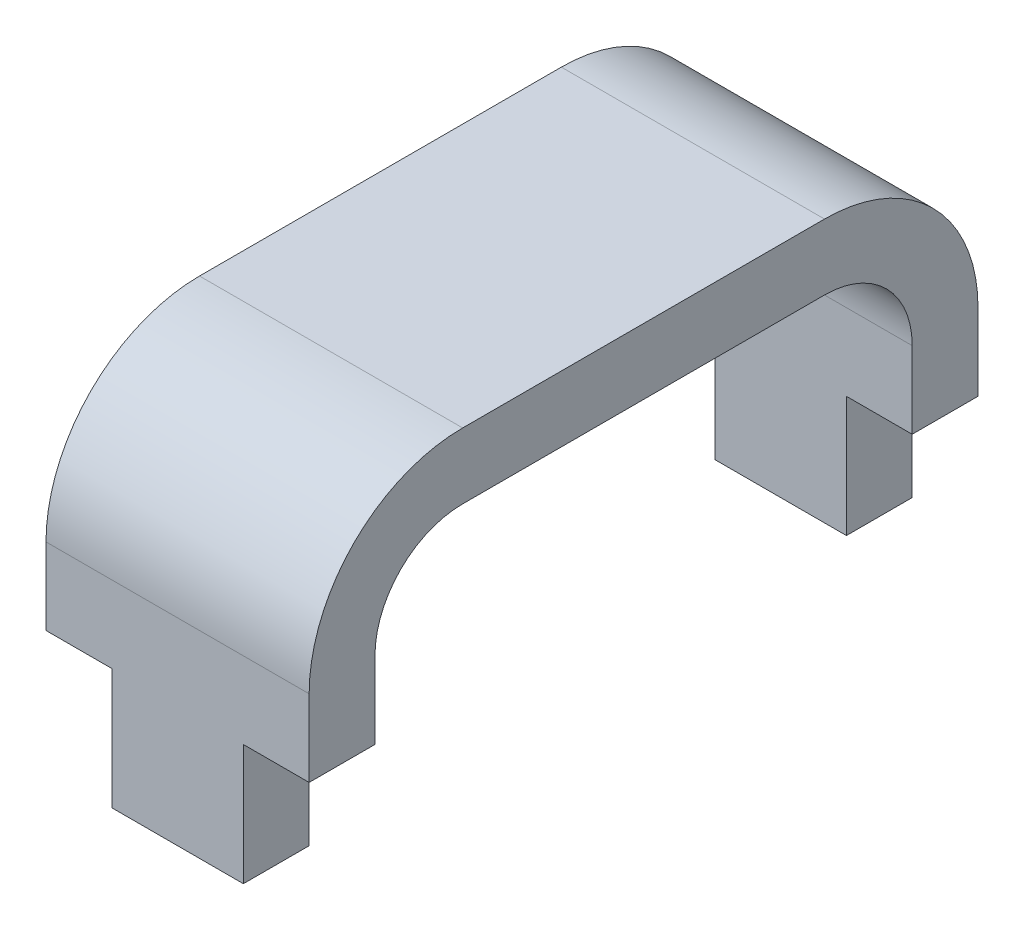
SolidWorks part; units mm, degrees
ref_plane "Front Plane" through (0, 0, 0) normal (0, 0, 1) x (1, 0, 0)
ref_plane "Top Plane" through (0, 0, 0) normal (0, 1, 0) x (1, 0, 0)
ref_plane "Right Plane" through (0, 0, 0) normal (1, 0, 0) x (0, 0, -1)
sketch "Sketch4" plane through (0, 0, 0) normal (1, 0, 0) x (0, 0, -1)
  line L0 (-13.3102, -12.5996) -> (-13.3102, -3.5996)
  line L1 (-9.3102, 3.4004) -> (7.1898, 3.4004)
  line L2 (-16.3102, -3.5996) -> (-16.3102, -12.5996)
  line L3 (-16.3102, -12.5996) -> (-13.3102, -12.5996)
  line L4 (14.1898, -3.5996) -> (14.1898, -12.5996)
  line L5 (-16.3102, 3.4004) -> (14.1898, -12.5996) construction
  line L6 (-16.3102, -12.5996) -> (14.1898, 3.4004) construction
  line L7 (-9.3102, 0.4004) -> (7.1898, 0.4004)
  line L8 (11.1898, -3.5996) -> (11.1898, -12.5996)
  line L9 (11.1898, -12.5996) -> (14.1898, -12.5996)
  arc A0 (11.1898, -3.5996) -> (7.1898, 0.4004) centre (7.1898, -3.5996) ccw
  arc A1 (-9.3102, 0.4004) -> (-13.3102, -3.5996) centre (-9.3102, -3.5996) ccw
  arc A2 (14.1898, -3.5996) -> (7.1898, 3.4004) centre (7.1898, -3.5996) ccw
  arc A3 (-9.3102, 3.4004) -> (-16.3102, -3.5996) centre (-9.3102, -3.5996) ccw
  point P0 (-1.0602, -4.5996)
  dimension "D5" = 4
  dimension "D6" = 7
  dimension "D1" = 30.5
  dimension "D2" = 3
  dimension "D3" = 3
  dimension "D4" = 3
  dimension "D7" = 16
extrude "Boss-Extrude1" add sketch "Sketch4" along normal blind 12
sketch "Sketch5" plane through (0, 0, 16.3102) normal (0, 0, 1) x (1, 0, 0)
  line L1 (0, -12.5996) -> (3, -12.5996)
  line L2 (0, -12.5996) -> (0, -7.0996)
  line L3 (0, -7.0996) -> (3, -7.0996)
  line L4 (3, -12.5996) -> (3, -7.0996)
  line L5 (12, -12.5996) -> (9, -12.5996)
  line L6 (12, -12.5996) -> (12, -7.0996)
  line L7 (12, -7.0996) -> (9, -7.0996)
  line L8 (9, -12.5996) -> (9, -7.0996)
  dimension "D1" = 3
  dimension "D2" = 5.5
  dimension "D3" = 5.5
  dimension "D4" = 3
extrude "Cut-Extrude1" cut sketch "Sketch5" against normal blind 52
